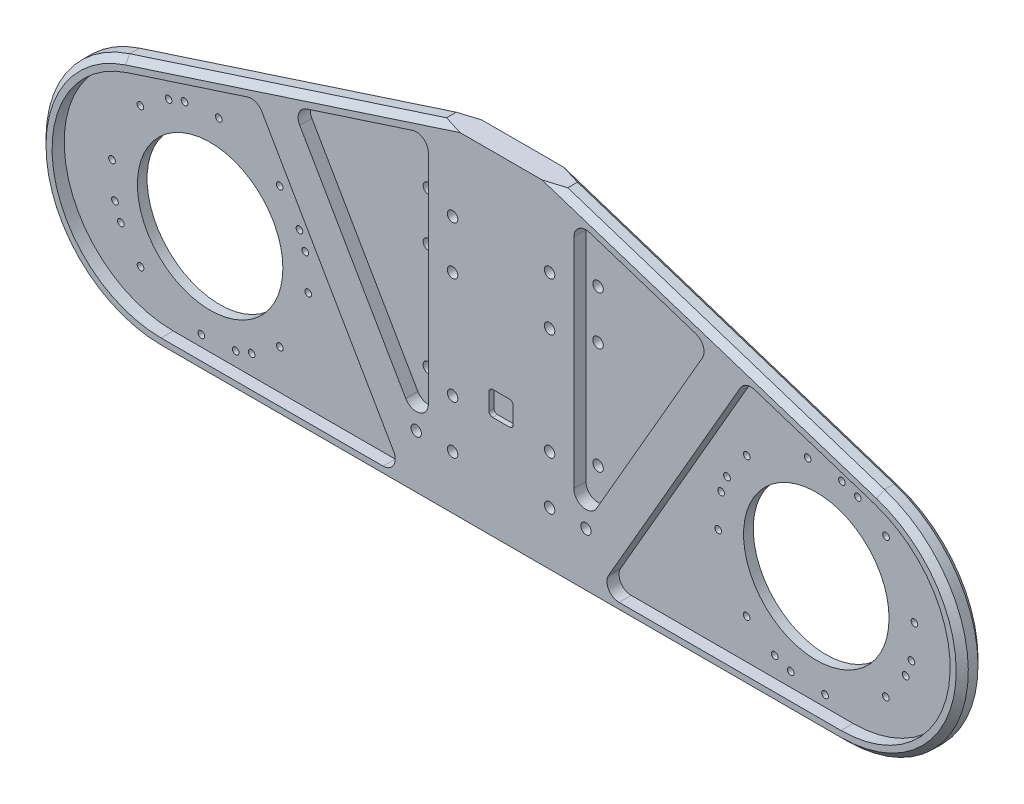
SolidWorks part; units mm, degrees
material "6061 合金"
ref_plane "前视基准面" through (0, 0, 0) normal (0, 0, 1) x (1, 0, 0)
ref_plane "上视基准面" through (0, 0, 0) normal (0, 1, 0) x (1, 0, 0)
ref_plane "右视基准面" through (0, 0, 0) normal (1, 0, 0) x (0, 0, -1)
other "Configuration Table"
sketch "草图1" plane through (0, 0, 0) normal (0, 0, 1) x (1, 0, 0)
  line L0 (0, 0) -> (0, 280) construction
  line L1 (0, 280) -> (861.7514, 0)
  line L3 (861.7514, 0) -> (0, 0)
  line L4 (-50, 352.899) -> (-50, -139.8009) construction
  line L5 (-961.7514, 0) -> (-100, 0)
  line L6 (-100, 280) -> (-961.7514, 0)
  line L7 (-100, 0) -> (-100, 280) construction
  line L8 (-100, 280) -> (0, 280)
  line L9 (0, 0) -> (-100, 0)
  circle A0 centre (200, 100) radius 85 construction
  circle A1 centre (200, 100) radius 60
  circle A2 centre (-300, 100) radius 85 construction
  circle A3 centre (-300, 100) radius 60
  dimension "D1" = 170
  dimension "D4" = 120
  dimension "D2" = 200
  dimension "D3" = 72
  dimension "D5" = 280
  dimension "D6" = 100
  dimension "D7" = 50
extrude "凸台-拉伸1" add sketch "草图1" along normal blind 8 contours L9 L3 L1 L8 L6 L5 A1 A3
fillet "圆角1" radius 100 2 edges at (861.7514, 0, 4) (-961.7514, 0, 4)
sketch "草图2" plane through (0, 0, 8) normal (0, 0, 1) x (1, 0, 0)
  line L0 (10, 266.2362) -> (10, 35.359)
  line L1 (30, 10) -> (230.3762, 10)
  line L2 (10, 266.2362) -> (122.2414, 229.7667)
  line L9 (10, 35.359) -> (122.2414, 229.7667)
  line L10 (30, 10) -> (151.4105, 220.2891)
  line L11 (151.4105, 220.2891) -> (258.1878, 185.5951)
  line L12 (10, 35.359) -> (10, 10) construction
  line L13 (10, 10) -> (30, 10) construction
  line L15 (0, 280) -> (261.2779, 195.1057) construction
  line L16 (230.3762, 0) -> (-330.3762, 0) construction
  line L19 (0, 280) -> (261.2779, 195.1057)
  line L24 (-50, 336.5114) -> (-50, -134.6936) construction
  line L29 (-100, 280) -> (0, 280) construction
  line L30 (230.3762, 0) -> (-330.3762, 0)
  line L31 (0, 280) -> (-100, 280)
  line L39 (-50, 280) -> (-50, 0)
  line L40 (-110, 10) -> (-130, 10) construction
  line L41 (-110, 35.359) -> (-110, 10) construction
  line L42 (-100, 280) -> (-361.2779, 195.1057)
  line L43 (-251.4105, 220.2891) -> (-358.1878, 185.5951)
  line L44 (-130, 10) -> (-251.4105, 220.2891)
  line L45 (-110, 35.359) -> (-222.2414, 229.7667)
  line L46 (-110, 266.2362) -> (-222.2414, 229.7667)
  line L47 (-130, 10) -> (-330.3762, 10)
  line L48 (-110, 266.2362) -> (-110, 35.359)
  arc A0 (230.3762, 10) -> (258.1878, 185.5951) centre (230.3762, 100) ccw
  arc A5 (230.3762, 0) -> (261.2779, 195.1057) centre (230.3762, 100) ccw construction
  arc A7 (230.3762, 0) -> (261.2779, 195.1057) centre (230.3762, 100) ccw
  arc A12 (-330.3762, 0) -> (-361.2779, 195.1057) centre (-330.3762, 100) cw
  arc A13 (-330.3762, 10) -> (-358.1878, 185.5951) centre (-330.3762, 100) cw
  point P33 (-50, 280)
  point P34 (-50, 0)
  line M64 (-100, 280) -> (-361.2779, 195.1057)
  arc M65 (-361.2779, 195.1057) -> (-330.3762, 0) centre (-330.3762, 100) ccw
  line M66 (-330.3762, 0) -> (230.3762, 0)
  arc M67 (230.3762, 0) -> (261.2779, 195.1057) centre (230.3762, 100) ccw
  line M68 (261.2779, 195.1057) -> (0, 280)
  line M69 (0, 280) -> (-100, 280)
  dimension "D4" = 10
  dimension "D2" = 10
  dimension "D3" = 10
  dimension "D6" = 30
  dimension "D7" = 60
  dimension "D8" = 20
  dimension "D1" = 10
extrude "凸台-拉伸2" add sketch "草图2" along normal blind 10 contours L39 L31 L46 L48 L45 L47 A13 L43 L44 M64 M65 M66 | L39 L30 A0 L1 L10 L11 L9 L0 L2 M69 M67 M68
fillet "圆角2" radius 10 10 edges at (10, 35.359, 13) (30, 10, 13) (122.2414, 229.7667, 13) (151.4105, 220.2891, 13) (10, 266.2362, 13) (-130, 10, 13) (-251.4105, 220.2891, 13) (-110, 266.2362, 13) (-222.2414, 229.7667, 13) (-110, 35.359, 13)
chamfer "倒角1" distance 5 angle 45 10 edges at (130.639, 237.5528, 0) (-50, 0, 0) (329.1451, 84.3566, 0) (-429.1451, 84.3566, 0) (-50, 0, 18) (329.1451, 84.3566, 18) (130.639, 237.5528, 18) (-230.639, 237.5528, 18) (-429.1451, 84.3566, 18) (-230.639, 237.5528, 0)
sketch "草图3" plane through (0, 0, 0) normal (0, 0, -1) x (-1, 0, 0)
  line L0 (134, 30) -> (100, 30) construction
  line L1 (-34, 236) -> (44, 236) construction
  line L2 (-34, 236) -> (-34, 158) construction
  line L3 (-34, 158) -> (44, 158) construction
  line L5 (-34, 108) -> (44, 108) construction
  line L6 (-34, 108) -> (-34, 30) construction
  line L7 (-34, 30) -> (0, 30) construction
  line L9 (134, 108) -> (134, 30) construction
  line L10 (330.3762, 0) -> (-230.3762, 0) construction
  line L11 (50, 335.2852) -> (50, -119.0767) construction
  line L12 (134, 108) -> (56, 108) construction
  line L13 (134, 158) -> (56, 158) construction
  line L14 (134, 236) -> (134, 158) construction
  line L15 (134, 236) -> (56, 236) construction
  circle A0 centre (-20, 217) radius 4.3
  circle A1 centre (-20, 177) radius 4.3
  circle A2 centre (10, 217) radius 4.3
  circle A3 centre (10, 177) radius 4.3
  circle A4 centre (-20, 89) radius 4.3
  circle A5 centre (10, 89) radius 4.3
  circle A6 centre (-20, 49) radius 4.3
  circle A7 centre (10, 49) radius 4.3
  circle A8 centre (300, 100) radius 60 construction
  circle A9 centre (-200, 100) radius 60 construction
  circle A10 centre (90, 49) radius 4.3
  circle A11 centre (120, 49) radius 4.3
  circle A12 centre (90, 89) radius 4.3
  circle A13 centre (120, 89) radius 4.3
  circle A14 centre (90, 177) radius 4.3
  circle A15 centre (90, 217) radius 4.3
  circle A16 centre (120, 177) radius 4.3
  circle A17 centre (120, 217) radius 4.3
  dimension "D7" = 8.6
  dimension "D16" = 8.6
  dimension "D1" = 78
  dimension "D2" = 78
  dimension "D3" = 30
  dimension "D4" = 78
  dimension "D5" = 30
  dimension "D6" = 50
  dimension "D8" = 19
  dimension "D9" = 19
  dimension "D10" = 19
  dimension "D11" = 19
  dimension "D12" = 14
  dimension "D13" = 14
  dimension "D14" = 40
  dimension "D17" = 19
  dimension "D18" = 19
  dimension "D19" = 19
  dimension "D20" = 19
  dimension "D21" = 14
  dimension "D22" = 14
extrude "切除-拉伸1" cut sketch "草图3" against normal through all both
sketch "草图4" plane through (0, 0, 8) normal (0, 0, 1) x (1, 0, 0)
  line L0 (-50, 330.4726) -> (-50, -61.6586) construction
  arc A0 (259.7806, 158.4465) -> (255.249, 156.3335) centre (257.5148, 157.39) ccw construction
  arc A1 (278.6673, 106.1128) -> (283.1989, 108.2258) centre (280.9331, 107.1693) ccw construction
  arc A2 (276.1928, 77.8292) -> (280.7244, 79.9423) centre (278.4586, 78.8857) ccw construction
  arc A3 (271.409, 64.6857) -> (275.9405, 66.7988) centre (273.6748, 65.7423) ccw construction
  arc A4 (255.1242, 41.4287) -> (259.6558, 43.5418) centre (257.39, 42.4852) ccw construction
  arc A5 (204.9035, 18.0104) -> (209.4351, 20.1235) centre (207.1693, 19.0669) ccw construction
  arc A6 (176.62, 20.4849) -> (181.1515, 22.598) centre (178.8857, 21.5414) ccw construction
  arc A7 (163.4765, 25.2687) -> (168.008, 27.3818) centre (165.7423, 26.3252) ccw construction
  arc A8 (140.2194, 41.5535) -> (144.751, 43.6665) centre (142.4852, 42.61) ccw construction
  arc A9 (121.3327, 93.8872) -> (116.8011, 91.7742) centre (119.0669, 92.8307) ccw construction
  arc A10 (123.8072, 122.1708) -> (119.2756, 120.0577) centre (121.5414, 121.1143) ccw construction
  arc A11 (128.591, 135.3143) -> (124.0595, 133.2012) centre (126.3252, 134.2577) ccw construction
  arc A12 (144.8758, 158.5713) -> (140.3442, 156.4582) centre (142.61, 157.5148) ccw construction
  arc A13 (195.0965, 181.9896) -> (190.5649, 179.8765) centre (192.8307, 180.9331) ccw construction
  arc A14 (223.38, 179.5151) -> (218.8485, 177.402) centre (221.1143, 178.4586) ccw construction
  arc A15 (236.5235, 174.7313) -> (231.992, 172.6182) centre (234.2577, 173.6748) ccw construction
  arc A16 (259.7806, 158.4465) -> (255.249, 156.3335) centre (257.5148, 157.39) ccw construction
  arc A17 (278.6673, 106.1128) -> (283.1989, 108.2258) centre (280.9331, 107.1693) ccw construction
  arc A18 (276.1928, 77.8292) -> (280.7244, 79.9423) centre (278.4586, 78.8857) ccw construction
  arc A19 (271.409, 64.6857) -> (275.9405, 66.7988) centre (273.6748, 65.7423) ccw construction
  arc A20 (255.1242, 41.4287) -> (259.6558, 43.5418) centre (257.39, 42.4852) ccw construction
  arc A21 (204.9035, 18.0104) -> (209.4351, 20.1235) centre (207.1693, 19.0669) ccw construction
  arc A22 (176.62, 20.4849) -> (181.1515, 22.598) centre (178.8857, 21.5414) ccw construction
  arc A23 (163.4765, 25.2687) -> (168.008, 27.3818) centre (165.7423, 26.3252) ccw construction
  arc A24 (140.2194, 41.5535) -> (144.751, 43.6665) centre (142.4852, 42.61) ccw construction
  arc A25 (121.3327, 93.8872) -> (116.8011, 91.7742) centre (119.0669, 92.8307) ccw construction
  arc A26 (123.8072, 122.1708) -> (119.2756, 120.0577) centre (121.5414, 121.1143) ccw construction
  arc A27 (128.591, 135.3143) -> (124.0595, 133.2012) centre (126.3252, 134.2577) ccw construction
  arc A28 (144.8758, 158.5713) -> (140.3442, 156.4582) centre (142.61, 157.5148) ccw construction
  arc A29 (195.0965, 181.9896) -> (190.5649, 179.8765) centre (192.8307, 180.9331) ccw construction
  arc A30 (223.38, 179.5151) -> (218.8485, 177.402) centre (221.1143, 178.4586) ccw construction
  arc A31 (236.5235, 174.7313) -> (231.992, 172.6182) centre (234.2577, 173.6748) ccw construction
  circle A32 centre (257.5148, 157.39) radius 2.75
  circle A33 centre (234.2577, 173.6748) radius 2.75
  circle A34 centre (221.1143, 178.4586) radius 2.75
  circle A35 centre (192.8307, 180.9331) radius 2.75
  circle A36 centre (142.61, 157.5148) radius 2.75
  circle A37 centre (126.3252, 134.2577) radius 2.75
  circle A38 centre (121.5414, 121.1143) radius 2.75
  circle A39 centre (119.0669, 92.8307) radius 2.75
  circle A40 centre (142.4852, 42.61) radius 2.75
  circle A41 centre (165.7423, 26.3252) radius 2.75
  circle A42 centre (178.8857, 21.5414) radius 2.75
  circle A43 centre (207.1693, 19.0669) radius 2.75
  circle A44 centre (257.39, 42.4852) radius 2.75
  circle A45 centre (273.6748, 65.7423) radius 2.75
  circle A46 centre (278.4586, 78.8857) radius 2.75
  circle A47 centre (280.9331, 107.1693) radius 2.75
  circle A48 centre (200, 100) radius 60 construction
  circle A49 centre (-300, 100) radius 60 construction
  arc A50 (-336.5235, 174.7313) -> (-331.992, 172.6182) centre (-334.2577, 173.6748) cw construction
  arc A51 (-323.38, 179.5151) -> (-318.8485, 177.402) centre (-321.1143, 178.4586) cw construction
  arc A52 (-295.0965, 181.9896) -> (-290.5649, 179.8765) centre (-292.8307, 180.9331) cw construction
  arc A53 (-244.8758, 158.5713) -> (-240.3442, 156.4582) centre (-242.61, 157.5148) cw construction
  arc A54 (-228.591, 135.3143) -> (-224.0595, 133.2012) centre (-226.3252, 134.2577) cw construction
  arc A55 (-223.8072, 122.1708) -> (-219.2756, 120.0577) centre (-221.5414, 121.1143) cw construction
  arc A56 (-221.3327, 93.8872) -> (-216.8011, 91.7742) centre (-219.0669, 92.8307) cw construction
  arc A57 (-240.2194, 41.5535) -> (-244.751, 43.6665) centre (-242.4852, 42.61) cw construction
  arc A58 (-263.4765, 25.2687) -> (-268.008, 27.3818) centre (-265.7423, 26.3252) cw construction
  arc A59 (-276.62, 20.4849) -> (-281.1515, 22.598) centre (-278.8857, 21.5414) cw construction
  arc A60 (-304.9035, 18.0104) -> (-309.4351, 20.1235) centre (-307.1693, 19.0669) cw construction
  arc A61 (-355.1242, 41.4287) -> (-359.6558, 43.5418) centre (-357.39, 42.4852) cw construction
  arc A62 (-371.409, 64.6857) -> (-375.9405, 66.7988) centre (-373.6748, 65.7423) cw construction
  arc A63 (-376.1928, 77.8292) -> (-380.7244, 79.9423) centre (-378.4586, 78.8857) cw construction
  arc A64 (-378.6673, 106.1128) -> (-383.1989, 108.2258) centre (-380.9331, 107.1693) cw construction
  arc A65 (-359.7806, 158.4465) -> (-355.249, 156.3335) centre (-357.5148, 157.39) cw construction
  circle A66 centre (-380.9331, 107.1693) radius 2.75
  circle A67 centre (-378.4586, 78.8857) radius 2.75
  circle A68 centre (-373.6748, 65.7423) radius 2.75
  circle A69 centre (-357.39, 42.4852) radius 2.75
  circle A70 centre (-307.1693, 19.0669) radius 2.75
  circle A71 centre (-278.8857, 21.5414) radius 2.75
  circle A72 centre (-265.7423, 26.3252) radius 2.75
  circle A73 centre (-242.4852, 42.61) radius 2.75
  circle A74 centre (-219.0669, 92.8307) radius 2.75
  circle A75 centre (-221.5414, 121.1143) radius 2.75
  circle A76 centre (-226.3252, 134.2577) radius 2.75
  circle A77 centre (-242.61, 157.5148) radius 2.75
  circle A78 centre (-292.8307, 180.9331) radius 2.75
  circle A79 centre (-321.1143, 178.4586) radius 2.75
  circle A80 centre (-334.2577, 173.6748) radius 2.75
  circle A81 centre (-357.5148, 157.39) radius 2.75
  dimension "D1" = 5.5
extrude "切除-拉伸2" cut sketch "草图4" against normal blind 10 contours A44 | A45 | A46 | A47 | A32 | A33 | A34 | A35 | A36 | A37 | A38 | A39 | A40 | A41 | A42 | A73 | A72 | A71 | A70 | A69 | A68 | A67 | A66 | A81 | A80 | A79 | A78 | A77 | A76 | A75 | A74 | A43
sketch "草图5" plane through (0, 0, 0) normal (0, 0, -1) x (-1, 0, 0)
  line L0 (50, 354.5789) -> (50, -118.9875) construction
  circle A0 centre (-192.8307, 180.9331) radius 6
  circle A1 centre (-142.61, 157.5148) radius 6
  circle A2 centre (-126.3252, 134.2577) radius 6
  circle A3 centre (-121.5414, 121.1143) radius 6
  circle A4 centre (-119.0669, 92.8307) radius 6
  circle A5 centre (-142.4852, 42.61) radius 6
  circle A6 centre (-165.7423, 26.3252) radius 6
  circle A7 centre (-178.8857, 21.5414) radius 6
  circle A8 centre (-207.1693, 19.0669) radius 6
  circle A9 centre (-257.39, 42.4852) radius 6
  circle A10 centre (-273.6748, 65.7423) radius 6
  circle A11 centre (-278.4586, 78.8857) radius 6
  circle A12 centre (-280.9331, 107.1693) radius 6
  circle A13 centre (-257.5148, 157.39) radius 6
  circle A14 centre (-234.2577, 173.6748) radius 6
  circle A15 centre (-221.1143, 178.4586) radius 6
  circle A16 centre (300, 100) radius 60 construction
  circle A17 centre (-200, 100) radius 60 construction
  circle A18 centre (321.1143, 178.4586) radius 6
  circle A19 centre (334.2577, 173.6748) radius 6
  circle A20 centre (357.5148, 157.39) radius 6
  circle A21 centre (380.9331, 107.1693) radius 6
  circle A22 centre (378.4586, 78.8857) radius 6
  circle A23 centre (373.6748, 65.7423) radius 6
  circle A24 centre (357.39, 42.4852) radius 6
  circle A25 centre (307.1693, 19.0669) radius 6
  circle A26 centre (278.8857, 21.5414) radius 6
  circle A27 centre (265.7423, 26.3252) radius 6
  circle A28 centre (242.4852, 42.61) radius 6
  circle A29 centre (219.0669, 92.8307) radius 6
  circle A30 centre (221.5414, 121.1143) radius 6
  circle A31 centre (226.3252, 134.2577) radius 6
  circle A32 centre (242.61, 157.5148) radius 6
  circle A33 centre (292.8307, 180.9331) radius 6
  dimension "D1" = 12
extrude "切除-拉伸3" cut sketch "草图5" against normal blind 4
sketch "草图6" plane through (0, 0, 18) normal (0, 0, 1) x (1, 0, 0)
  line L0 (-50, 324.4003) -> (-50, -115.846) construction
  line L1 (-300, 100) -> (200, 100) construction
  line L3 (-60, 110) -> (-40, 110)
  line L4 (-60, 110) -> (-60, 90)
  line L5 (-60, 90) -> (-40, 90)
  line L6 (-40, 110) -> (-40, 90)
  circle A0 centre (200, 100) radius 60 construction
  circle A1 centre (-300, 100) radius 60 construction
  dimension "D1" = 20
  dimension "D2" = 20
extrude "切除-拉伸4" cut sketch "草图6" against normal blind 4
fillet "圆角3" radius 3 4 edges at (-40, 90, 16) (-60, 90, 16) (-60, 110, 16) (-40, 110, 16)
